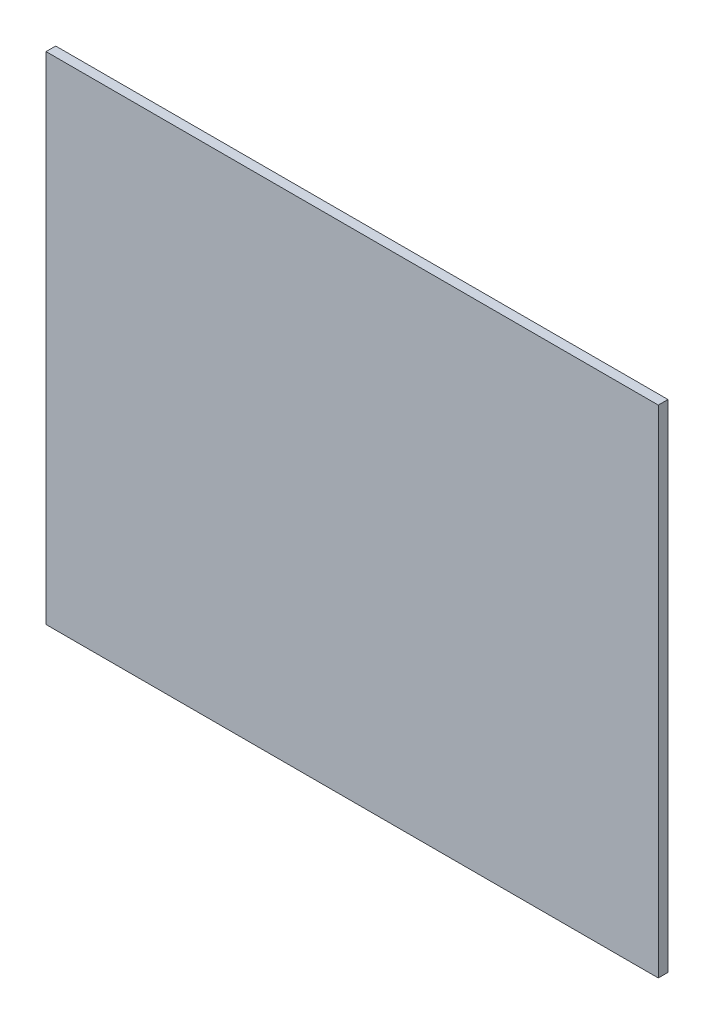
SolidWorks part; units mm, degrees
ref_plane "Front Plane" through (0, 0, 0) normal (0, 0, 1) x (1, 0, 0)
ref_plane "Top Plane" through (0, 0, 0) normal (0, 1, 0) x (1, 0, 0)
ref_plane "Right Plane" through (0, 0, 0) normal (1, 0, 0) x (0, 0, -1)
sketch "Sketch2" plane through (0, 0, 0) normal (0, 0, 1) x (1, 0, 0)
  line L1 (-32.3159, 17.6007) -> (30.9841, 17.6007)
  line L2 (-32.3159, 17.6007) -> (-32.3159, -33.6993)
  line L3 (-32.3159, -33.6993) -> (30.9841, -33.6993)
  line L4 (30.9841, 17.6007) -> (30.9841, -33.6993)
  dimension "D1" = 63.3
  dimension "D2" = 51.3
extrude "Boss-Extrude1" add sketch "Sketch2" along normal blind 1
